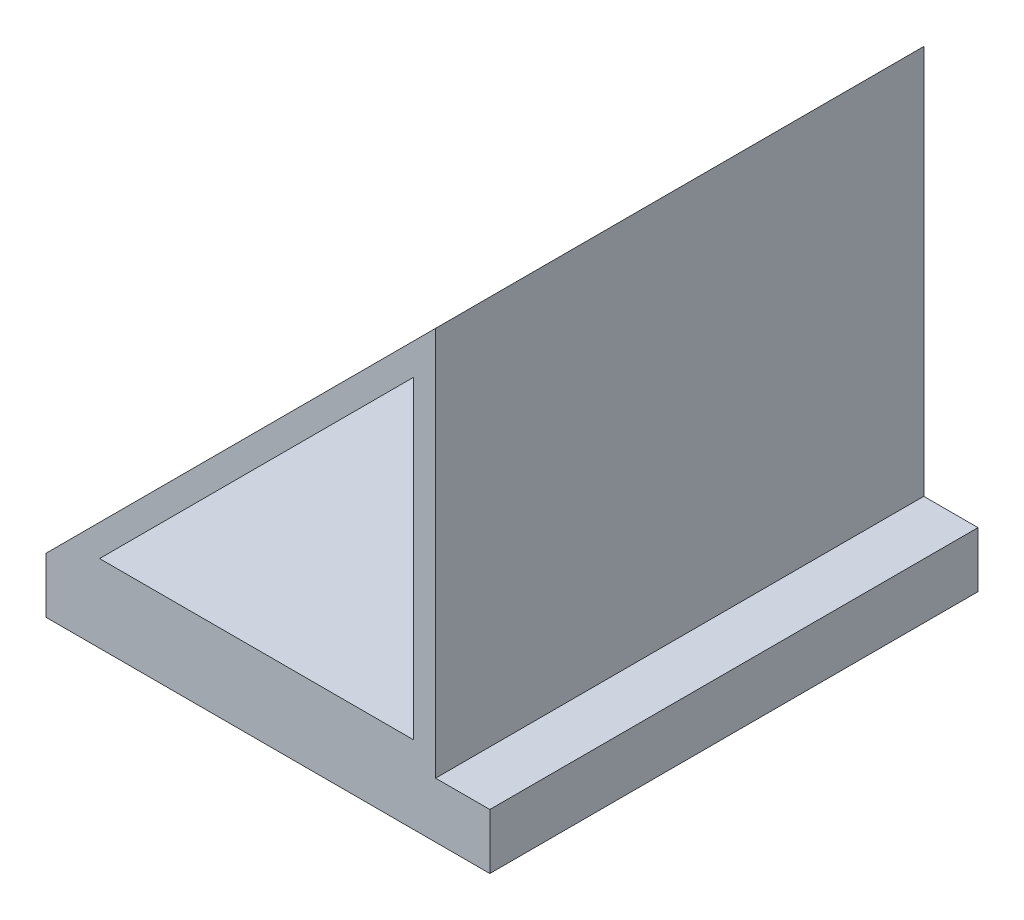
SolidWorks part; units mm, degrees
ref_plane "Front Plane" through (0, 0, 0) normal (0, 0, 1) x (1, 0, 0)
ref_plane "Top Plane" through (0, 0, 0) normal (0, 1, 0) x (1, 0, 0)
ref_plane "Right Plane" through (0, 0, 0) normal (1, 0, 0) x (0, 0, -1)
sketch "Sketch1" plane through (0, 0, 0) normal (0, 0, 1) x (1, 0, 0)
  line L0 (0, 0) -> (-28.2843, -28.2843)
  line L1 (-28.2843, -28.2843) -> (0, -28.2843)
  line L2 (0, -28.2843) -> (0, 0)
  line L3 (2, 4.8284) -> (-33.1127, -30.2843)
  line L4 (-33.1127, -30.2843) -> (2, -30.2843)
  line L5 (2, -30.2843) -> (2, 4.8284)
  dimension "D1" = 40
  dimension "D2" = 45
  dimension "D3" = 2
extrude "Boss-Extrude1" add sketch "Sketch1" along normal blind 44
sketch "Sketch2" plane through (-1.4142, 1.4142, 0) normal (-0.7071, 0.7071, 0) x (0, 0, 1)
  line L0 (44, -40) -> (0, -40) construction
  line L1 (44, 4.8284) -> (44, -44.8284) construction
  line L2 (0, 4.8284) -> (0, -44.8284) construction
  line L3 (44, 0) -> (0, 0) construction
  line L4 (0, -40) -> (44, 0) construction
  line L5 (6, -4) -> (38, -4) construction
  line L6 (6, -4) -> (6, -36) construction
  line L7 (6, -36) -> (38, -36) construction
  line L8 (38, -4) -> (38, -36) construction
  line L9 (6, -4) -> (38, -36) construction
  circle A0 centre (6, -36) radius 1.5
  circle A1 centre (6, -4) radius 1.5
  circle A2 centre (38, -36) radius 1.5
  circle A3 centre (38, -4) radius 1.5
  circle A4 centre (22, -20) radius 17
  point P17 (22, -20)
  dimension "D2" = 3
  dimension "D4" = 34
  dimension "D1" = 40
  dimension "D3" = 32
extrude "Cut-Extrude1" cut sketch "Sketch2" against normal up to next
sketch "Sketch3" plane through (0, 0, 0) normal (0, 0, 1) x (1, 0, 0)
  line L1 (-33.1127, -30.2843) -> (6.8873, -30.2843)
  line L2 (-33.1127, -30.2843) -> (-33.1127, -35.2843)
  line L3 (-33.1127, -35.2843) -> (6.8873, -35.2843)
  line L4 (6.8873, -30.2843) -> (6.8873, -35.2843)
  dimension "D1" = 5
  dimension "D2" = 40
extrude "Boss-Extrude2" add sketch "Sketch3" along normal up to surface (44 mm away) up to face at (-9.7042, -18.58, 44)
